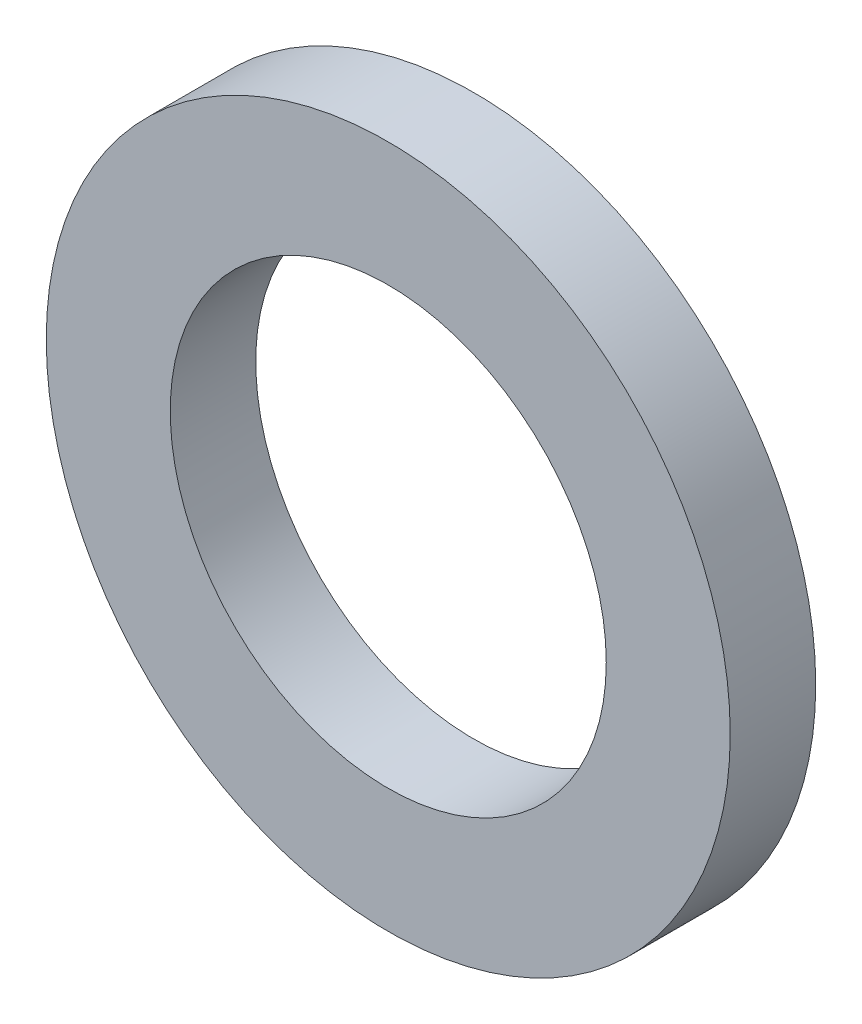
SolidWorks part; units mm, degrees
material "201 Annealed Stainless Steel (SS)"
ref_plane "Plano frontal" through (0, 0, 0) normal (0, 0, 1) x (1, 0, 0)
ref_plane "Plano superior" through (0, 0, 0) normal (0, 1, 0) x (1, 0, 0)
ref_plane "Plano direito" through (0, 0, 0) normal (1, 0, 0) x (0, 0, -1)
sketch "Esboço1" plane through (0, 0, 0) normal (0, 0, 1) x (1, 0, 0)
  circle A0 centre (0, 0) radius 2.55
  circle A1 centre (0, 0) radius 4
  dimension "D1" = 5.1
extrude "Ressalto-extrusão1" add sketch "Esboço1" along normal blind 1
